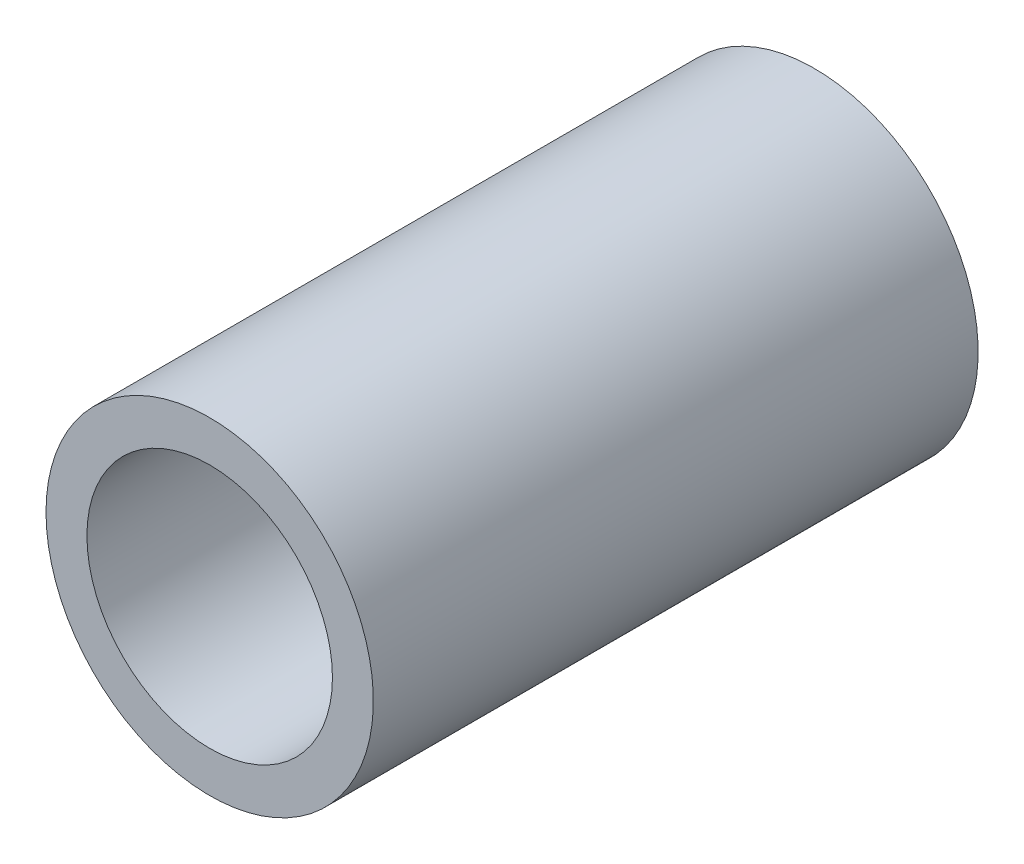
SolidWorks part; units mm, degrees
material "Acrylic (Medium-high impact)"
ref_plane "Front Plane" through (0, 0, 0) normal (0, 0, 1) x (1, 0, 0)
ref_plane "Top Plane" through (0, 0, 0) normal (0, 1, 0) x (1, 0, 0)
ref_plane "Right Plane" through (0, 0, 0) normal (1, 0, 0) x (0, 0, -1)
sketch "Sketch1" plane through (0, 0, 0) normal (0, 0, 1) x (1, 0, 0)
  circle A0 centre (0, 0) radius 3
  circle A1 centre (0, 0) radius 4
  dimension "D1" = 6
  dimension "D2" = 8
extrude "Boss-Extrude1" add sketch "Sketch1" along normal blind 14.78
